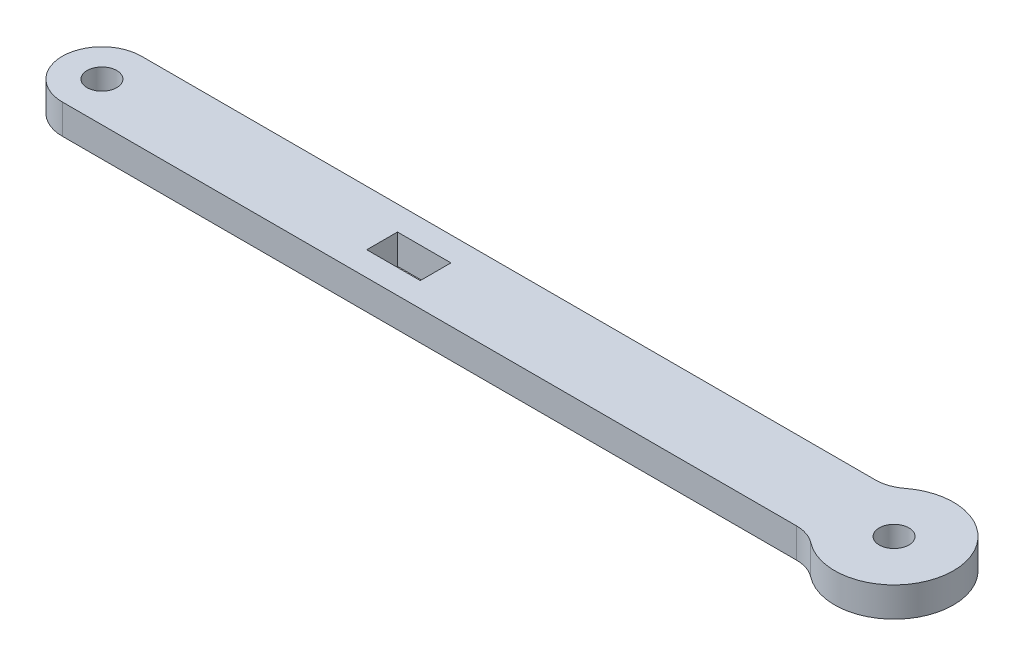
SolidWorks part; units mm, degrees
material "Acrílico (médio-alto impacto)"
ref_plane "Plano frontal" through (0, 0, 0) normal (0, 0, 1) x (1, 0, 0)
ref_plane "Plano superior" through (0, 0, 0) normal (0, 1, 0) x (1, 0, 0)
ref_plane "Plano direito" through (0, 0, 0) normal (1, 0, 0) x (0, 0, -1)
sketch "Esboço1" plane through (0, 0, 0) normal (0, 1, 0) x (1, 0, 0)
  line L0 (0, 0) -> (80, 0) construction
  line L1 (0, 4) -> (74.1348, 4)
  line L2 (0, -4) -> (74.1348, -4)
  arc A0 (0, -4) -> (0, 4) centre (0, 0) cw
  arc A1 (76.3343, -4.75) -> (76.3343, 4.75) centre (80, 0) ccw
  arc A2 (74.1348, 4) -> (76.3343, 4.75) centre (74.1348, 7.6) ccw
  arc A3 (74.1348, -4) -> (76.3343, -4.75) centre (74.1348, -7.6) cw
  dimension "D2" = 8
  dimension "D3" = 12
  dimension "D4" = 3.6
  dimension "D1" = 80
sketch "Esboço2" plane through (0, 0, 0) normal (0, 1, 0) x (1, 0, 0)
  line L0 (0, 0) -> (80, 0) construction
  line L1 (33.7, 1.55) -> (28.3, 1.55)
  line L2 (33.7, 1.55) -> (33.7, -1.55)
  line L3 (33.7, -1.55) -> (28.3, -1.55)
  line L4 (28.3, 1.55) -> (28.3, -1.55)
  line L5 (31, -1.55) -> (31, 1.55) construction
  line L6 (33.7, 0) -> (28.3, 0) construction
  point P0 (31, 0)
  dimension "D1" = 3.1
  dimension "D2" = 5.4
  dimension "D3" = 28.3
extrude "Ressalto-extrusão1" add sketch "Esboço1" against normal blind 3
extrude "Corte-extrusão1" cut sketch "Esboço2" against normal through all
hole_wizard "Furo de diâmetro Ø3.0 (3)1" positions "Esboço3" profile "Esboço4" hole size "Ø3.0" standard "ISO" end condition through all
sketch "Esboço3" plane through (0, 0, 0) normal (0, 1, 0) x (1, 0, 0)
  point P0 (0, 0)
  point P3 (80, 0)
sketch "Esboço4" plane through (0, 0, 0) normal (1, 0, 0) x (0, 0, 1)
  line L0 (0, 0) -> (0, 3)
  line L1 (0, 3) -> (1.5, 3)
  line L2 (1.5, 3) -> (1.5, 0)
  line L5 (1.5, 0) -> (0, 0)
  line L11 (0, -6.35) -> (0, 107.95) construction
  dimension "Thru Hole Dia." = 3
  dimension "Thru Hole Depth" = 3
